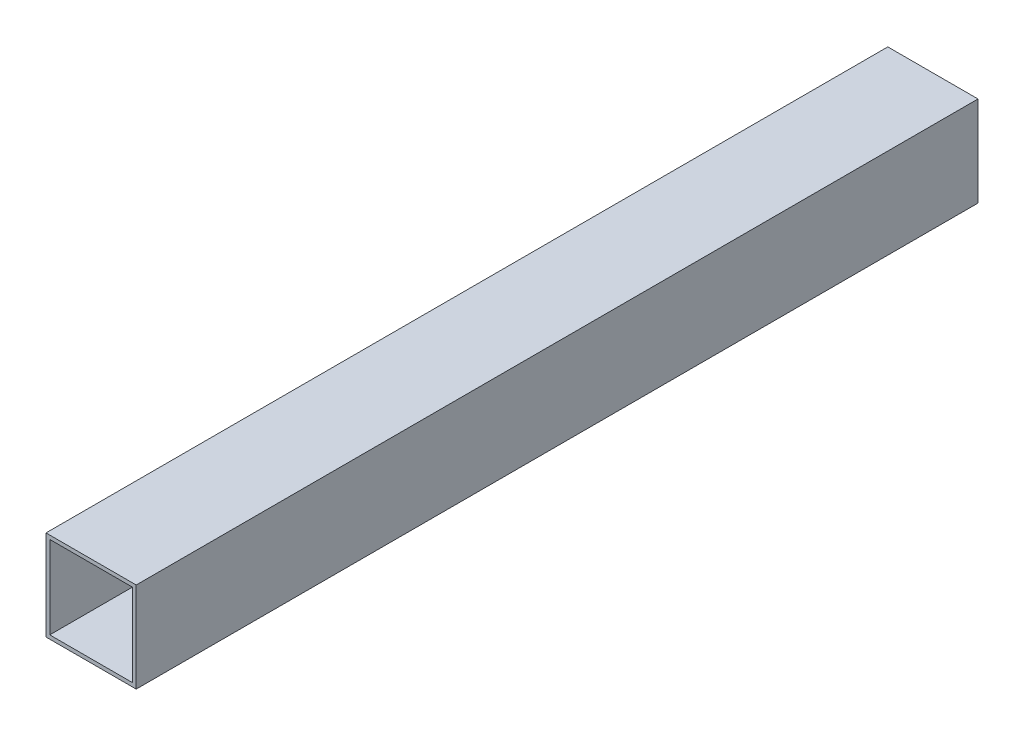
SolidWorks part; units mm, degrees
material "Custom Plastic"
ref_plane "Front Plane" through (0, 0, 0) normal (0, 0, 1) x (1, 0, 0)
ref_plane "Top Plane" through (0, 0, 0) normal (0, 1, 0) x (1, 0, 0)
ref_plane "Right Plane" through (0, 0, 0) normal (1, 0, 0) x (0, 0, -1)
sketch "Sketch2" plane through (0, 0, 0) normal (0, 0, 1) x (1, 0, 0)
  line L9 (-40.7297, 18.631) -> (35.4703, 18.631)
  line L10 (-40.7297, 18.631) -> (-40.7297, -57.569)
  line L11 (-40.7297, -57.569) -> (35.4703, -57.569)
  line L12 (35.4703, 18.631) -> (35.4703, -57.569)
extrude "Boss-Extrude1" add sketch "Sketch2" along normal blind 711.2 contours L10 L11 L12 L9
sketch "Sketch3" plane through (0, 0, 711.2) normal (0, 0, 1) x (1, 0, 0)
  line L0 (35.4703, 18.631) -> (35.4703, -57.569) construction
  line L1 (-40.7297, -57.569) -> (35.4703, -57.569) construction
  line L2 (-40.7297, 18.631) -> (-40.7297, -57.569) construction
  line L3 (-40.7297, 18.631) -> (35.4703, 18.631) construction
  line L4 (35.4703, 18.631) -> (35.4703, -57.569)
  line L5 (-40.7297, -57.569) -> (35.4703, -57.569)
  line L6 (-40.7297, 18.631) -> (-40.7297, -57.569)
  line L7 (-40.7297, 18.631) -> (35.4703, 18.631)
  line L9 (-37.5547, 15.456) -> (32.2953, 15.456)
  line L10 (-37.5547, 15.456) -> (-37.5547, -54.394)
  line L11 (-37.5547, -54.394) -> (32.2953, -54.394)
  line L12 (32.2953, 15.456) -> (32.2953, -54.394)
  dimension "D1" = 69.85
  dimension "D2" = 69.85
  dimension "D3" = 3.175
  dimension "D4" = 3.175
extrude "Cut-Extrude1" cut sketch "Sketch3" against normal blind 711.2 contours L10 L11 L12 L9
